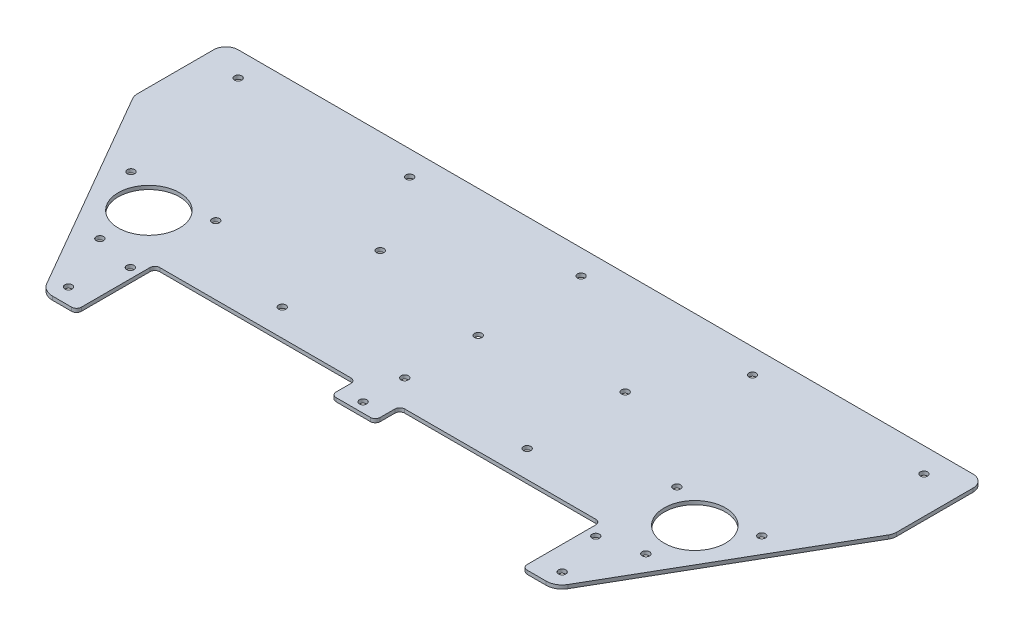
SolidWorks part; units mm, degrees
material "3.0205 (EN-AW 1200)"
ref_plane "Plan de face" through (0, 0, 0) normal (0, 0, 1) x (1, 0, 0)
ref_plane "Plan de dessus" through (0, 0, 0) normal (0, 1, 0) x (1, 0, 0)
ref_plane "Plan de droite" through (0, 0, 0) normal (1, 0, 0) x (0, 0, -1)
sketch "Esquisse1" plane through (0, 0, 0) normal (0, 1, 0) x (1, 0, 0)
  line L0 (0, 0) -> (0, -160) construction
  line L1 (-155, -35) -> (155, -35)
  line L2 (-155, -35) -> (-155, -72.5622)
  line L3 (-100.765, -160) -> (100.765, -160)
  line L4 (155, -72.5622) -> (106.3941, -156.75)
  line L5 (-155, -72.5622) -> (-106.3941, -156.75)
  line L6 (155, -35) -> (155, -72.5622)
  line L7 (158.5, -53.5) -> (100.765, -153.5) construction
  line L8 (94.1254, -100) -> (111.446, -110) construction
  circle A0 centre (-70, -45) radius 1.5
  circle A1 centre (0, -45) radius 1.5
  circle A2 centre (111.446, -110) radius 12.5
  circle A3 centre (128.7665, -100) radius 1.5
  circle A4 centre (94.1254, -100) radius 1.5
  circle A5 centre (111.446, -130) radius 1.5
  circle A6 centre (111.446, -110) radius 20 construction
  circle A7 centre (70, -45) radius 1.5
  circle A8 centre (-140, -45) radius 1.5
  circle A9 centre (140, -45) radius 1.5
  arc A10 (100.765, -160) -> (106.3941, -156.75) centre (100.765, -153.5) ccw
  arc A11 (-106.3941, -156.75) -> (-100.765, -160) centre (-100.765, -153.5) ccw
  circle A12 centre (-100.765, -153.5) radius 1.5
  circle A13 centre (100.765, -153.5) radius 1.5
  circle A14 centre (-111.446, -130) radius 1.5
  circle A15 centre (-128.7665, -100) radius 1.5
  circle A16 centre (-111.446, -110) radius 12.5
  circle A17 centre (-94.1254, -100) radius 1.5
  point P30 (104.5177, -160)
  point P33 (-104.5177, -160)
  dimension "D2" = 70
  dimension "D3" = 10
  dimension "D4" = 3
  dimension "D5" = 45
  dimension "D7" = 120
  dimension "D8" = 40
  dimension "D10" = 3
  dimension "D11" = 25
  dimension "D12" = 310
  dimension "D15" = 70
  dimension "D16" = 6.5
  dimension "D18" = 3
  dimension "D19" = 8.5
  dimension "D20" = 18.5
  dimension "D21" = 50
  dimension "D22" = 19
  dimension "D6" = 160
  dimension "D9" = 120
  dimension "D13" = 60
  dimension "D14" = 201.5299
  dimension "D17" = 209.0355
extrude "Boss.-Extru.1" add sketch "Esquisse1" along normal blind 1.5
fillet "Congé2" radius 5 4 edges at (155, 0.75, 72.5622) (155, 0.75, 35) (-155, 0.75, 35) (-155, 0.75, 72.5622)
sketch "Esquisse2" plane through (0, 1.5, 0) normal (0, 1, 0) x (1, 0, 0)
  line L0 (-100.765, -160) -> (100.765, -160) construction
  line L1 (-91, -160) -> (91, -160)
  line L2 (-91, -160) -> (-91, -128)
  line L3 (-91, -128) -> (91, -128)
  line L5 (0, 0) -> (0, -35) construction
  line L6 (150, -35) -> (-150, -35) construction
  line L9 (91, -160) -> (91, -128)
  circle A0 centre (-50, -77) radius 1.5
  circle A1 centre (-50, -117) radius 1.5
  circle A2 centre (50, -117) radius 1.5
  circle A3 centre (50, -77) radius 1.5
  circle A4 centre (0, -117) radius 1.5
  circle A5 centre (0, -87) radius 1.5
  dimension "D3" = 40
  dimension "D4" = 3
  dimension "D5" = 100
  dimension "D6" = 11
  dimension "D7" = 30
  dimension "D1" = 32
  dimension "D2" = 182
extrude "Enlèv. mat.-Extru.1" cut sketch "Esquisse2" against normal through all
sketch "Esquisse3" plane through (0, 1.5, 0) normal (0, 1, 0) x (1, 0, 0)
  line L0 (91, -128) -> (-91, -128) construction
  line L1 (-9, -138) -> (9, -138)
  line L2 (-9, -138) -> (-9, -128)
  line L3 (-9, -128) -> (9, -128)
  line L4 (9, -138) -> (9, -128)
  point P4 (0, -128)
  dimension "D1" = 18
  dimension "D2" = 10
extrude "Boss.-Extru.2" add sketch "Esquisse3" against normal up to surface (1.5 mm away) up to face at (0, 0, 88.5)
fillet "Congé3" radius 2 8 edges at (91, 0.75, 160) (-91, 0.75, 128) (-91, 0.75, 160) (91, 0.75, 128) (9, 0.75, 128) (9, 0.75, 138) (-9, 0.75, 138) (-9, 0.75, 128)
sketch "Esquisse4" plane through (0, 1.5, 0) normal (0, 1, 0) x (1, 0, 0)
  line L0 (0, 0) -> (0, -138) construction
  line L1 (-7, -138) -> (7, -138) construction
  line L2 (-11, -128) -> (-89, -128) construction
  circle A1 centre (-95, -134) radius 1.5
  circle A2 centre (0, -134) radius 1.5
  circle A4 centre (95, -134) radius 1.5
  dimension "D1" = 6
  dimension "D2" = 3
  dimension "D4" = 95
extrude "Enlèv. mat.-Extru.2" cut sketch "Esquisse4" against normal blind 3
